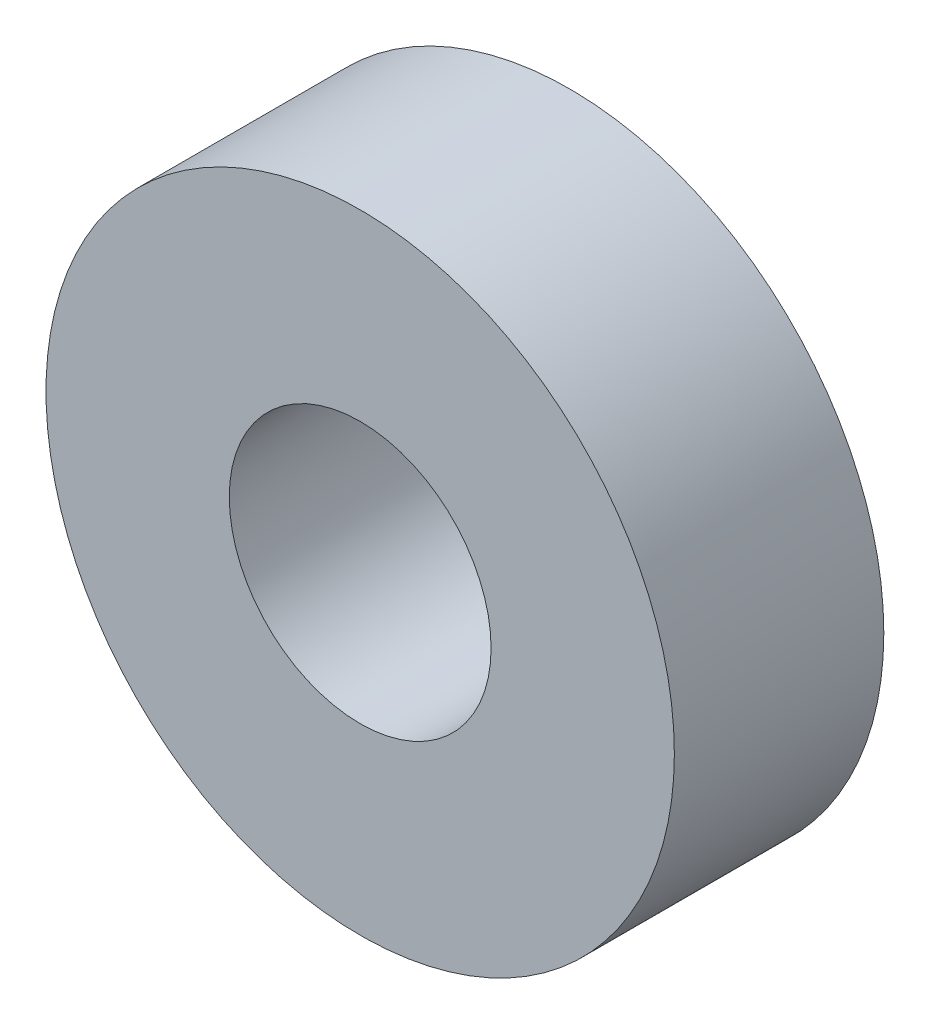
SolidWorks part; units mm, degrees
ref_plane "前视基准面" through (0, 0, 0) normal (0, 0, 1) x (1, 0, 0)
ref_plane "上视基准面" through (0, 0, 0) normal (0, 1, 0) x (1, 0, 0)
ref_plane "右视基准面" through (0, 0, 0) normal (1, 0, 0) x (0, 0, -1)
sketch "草图1" plane through (0, 0, 0) normal (0, 0, 1) x (1, 0, 0)
  circle A0 centre (0, 0) radius 2.5
  circle A1 centre (0, 0) radius 6
  dimension "D1" = 5
  dimension "D2" = 12
extrude "凸台-拉伸1" add sketch "草图1" along normal mid plane 4
